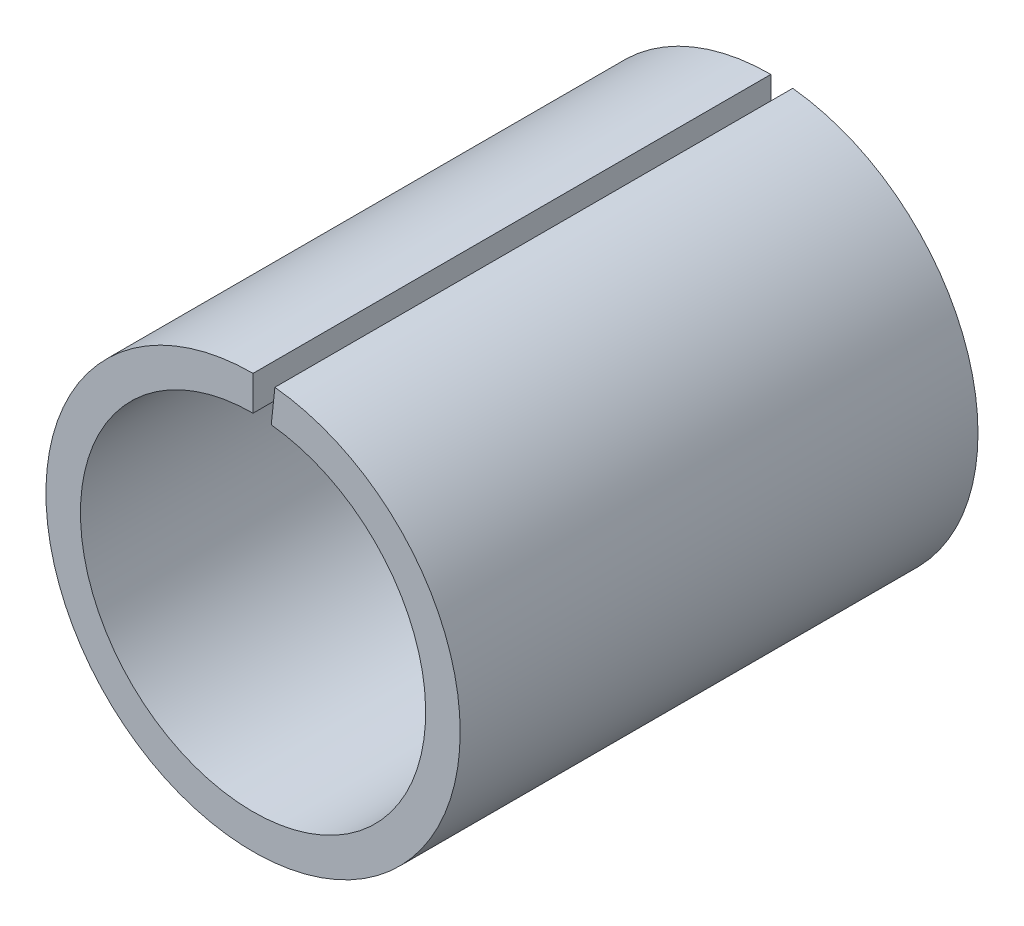
SolidWorks part; units mm, degrees
ref_plane "前视基准面" through (0, 0, 0) normal (0, 0, 1) x (1, 0, 0)
ref_plane "上视基准面" through (0, 0, 0) normal (0, 1, 0) x (1, 0, 0)
ref_plane "右视基准面" through (0, 0, 0) normal (1, 0, 0) x (0, 0, -1)
sketch "草图1" plane through (0, 0, 0) normal (0, 0, 1) x (1, 0, 0)
  circle A0 centre (0, 0) radius 5
  circle A1 centre (0, 0) radius 6
  dimension "D1" = 12
  dimension "D2" = 10
extrude "凸台-拉伸1" add sketch "草图1" along normal blind 15
sketch "草图2" plane through (0, 0, 15) normal (0, 0, 1) x (1, 0, 0)
  line L0 (0, 0) -> (0, 6)
  line L1 (0, 6) -> (0.8178, 7.7172)
  line L2 (0.8178, 7.7172) -> (0, 0)
  circle A0 centre (0, 0) radius 6 construction
  point P6 (0.8178, 7.7172)
extrude "切除-拉伸1" cut sketch "草图2" against normal blind 100
